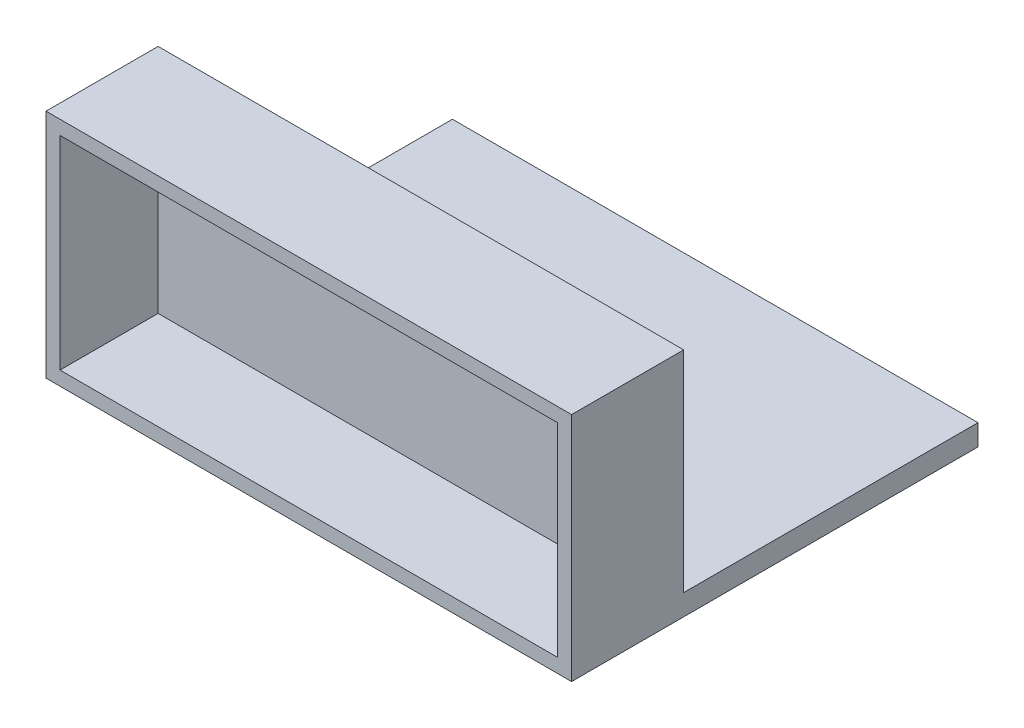
SolidWorks part; units mm, degrees
ref_plane "Front Plane" through (0, 0, 0) normal (0, 0, 1) x (1, 0, 0)
ref_plane "Top Plane" through (0, 0, 0) normal (0, 1, 0) x (1, 0, 0)
ref_plane "Right Plane" through (0, 0, 0) normal (1, 0, 0) x (0, 0, -1)
sketch "Sketch1" plane through (0, 0, 0) normal (0, 1, 0) x (1, 0, 0)
  line L1 (-75, 50) -> (75, 50)
  line L2 (-75, 50) -> (-75, -62)
  line L3 (-75, -62) -> (75, -62)
  line L4 (75, 50) -> (75, -62)
  dimension "D1" = 150
  dimension "D2" = 112
  dimension "D3" = 50
  dimension "D4" = 75
extrude "Boss-Extrude1" add sketch "Sketch1" along normal blind 6
sketch "Sketch3" plane through (0, 0, 62) normal (0, 0, 1) x (1, 0, 0)
  line L4 (-75, 0) -> (75, 0)
  line L5 (75, 0) -> (75, 6)
  line L6 (75, 6) -> (-75, 6)
  line L7 (-75, 6) -> (-75, 0)
  line L8 (-75, 0) -> (75, 0)
  line L9 (75, 0) -> (75, 6)
  line L10 (75, 6) -> (-75, 6)
  line L11 (-75, 6) -> (-75, 0)
  dimension "D1" = 0
extrude "Boss-Extrude2" add sketch "Sketch3" along normal up to surface (8 mm away)
sketch "Sketch4" plane through (0, 0, 0) normal (0, -1, 0) x (-1, 0, 0)
  line L0 (-75, -70) -> (-75, 50) construction
  line L1 (75, -70) -> (-75, -70)
  line L2 (75, -70) -> (75, -66)
  line L3 (75, -66) -> (-75, -66)
  line L4 (-75, -70) -> (-75, -66)
  line L5 (86, -66) -> (-86, -66) construction
extrude "Boss-Extrude3" add sketch "Sketch4" along normal up to surface (8 mm away)
sketch "Sketch6" plane through (0, 6, 0) normal (0, 1, 0) x (1, 0, 0)
  line L0 (75, -70) -> (75, 50) construction
  line L1 (-75, -70) -> (75, -70)
  line L2 (-75, -70) -> (-75, -34)
  line L3 (-75, -34) -> (75, -34)
  line L4 (75, -70) -> (75, -34)
  line L5 (100, -34) -> (-100, -34) construction
extrude "Boss-Extrude4" add sketch "Sketch6" along normal blind 60
sketch "Sketch7" plane through (0, 0, 70) normal (0, 0, 1) x (1, 0, 0)
  line L4 (-75, 66) -> (-75, -8)
  line L5 (-75, -8) -> (75, -8)
  line L6 (75, -8) -> (75, 66)
  line L7 (75, 66) -> (-75, 66)
  line L8 (-75, 66) -> (-75, -8)
  line L9 (-75, -8) -> (75, -8)
  line L10 (75, -8) -> (75, 66)
  line L11 (75, 66) -> (-75, 66)
  dimension "D1" = 0
extrude "Cut-Extrude1" cut sketch "Sketch7" against normal up to surface (4 mm away)
sketch "Sketch8" plane through (0, 0, 66) normal (0, 0, 1) x (1, 0, 0)
  line L1 (-71, 62) -> (71, 62)
  line L2 (-71, 62) -> (-71, 4)
  line L3 (-71, 4) -> (71, 4)
  line L4 (71, 62) -> (71, 4)
  line L5 (75, 66) -> (-75, 66) construction
  dimension "D1" = 4
  dimension "D2" = 4
  dimension "D3" = 4
  dimension "D4" = 4
extrude "Cut-Extrude2" cut sketch "Sketch8" against normal blind 28
